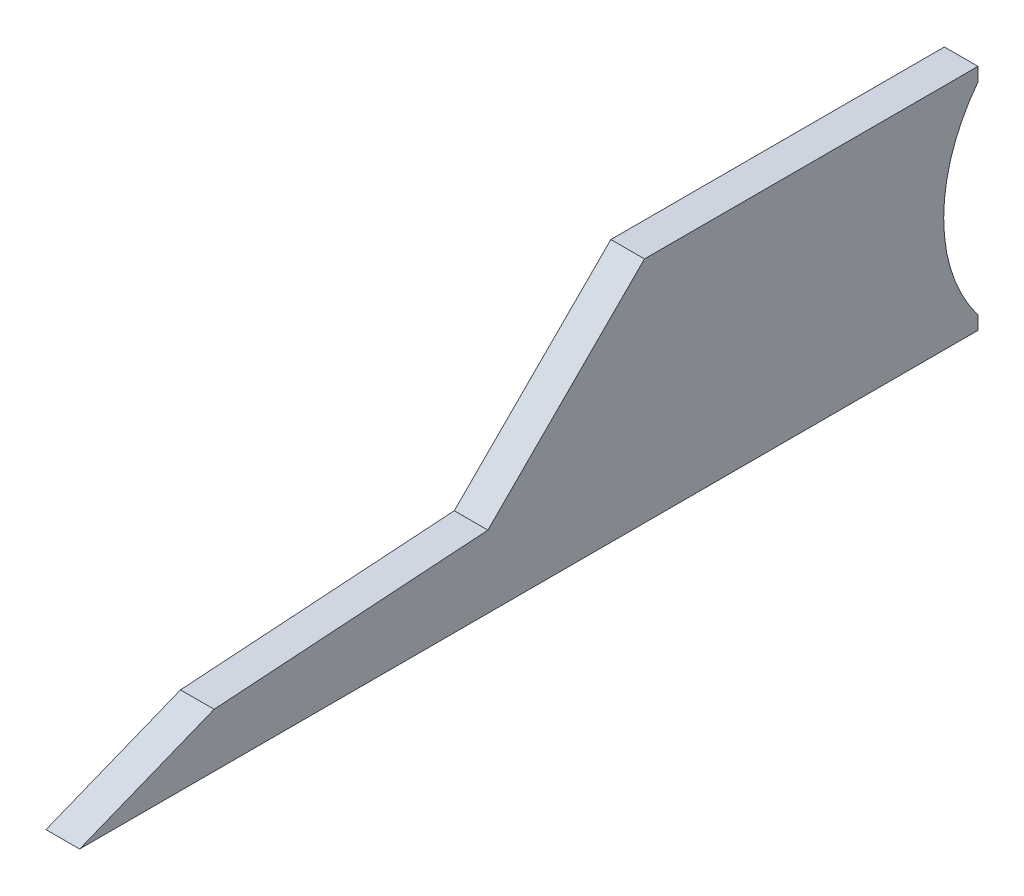
SolidWorks part; units mm, degrees
ref_plane "Front Plane" through (0, 0, 0) normal (0, 0, 1) x (1, 0, 0)
ref_plane "Top Plane" through (0, 0, 0) normal (0, 1, 0) x (1, 0, 0)
ref_plane "Right Plane" through (0, 0, 0) normal (1, 0, 0) x (0, 0, -1)
sketch "Sketch1" plane through (0, 0, 0) normal (1, 0, 0) x (0, 0, -1)
  line L0 (-106.172, 0) -> (-62.992, 43.18)
  line L1 (0, 0) -> (-106.172, 0)
  line L2 (0, 0) -> (0, 2.54)
  line L3 (0, 43.18) -> (-62.992, 43.18)
  line L5 (0, 40.64) -> (-65.532, 40.64) construction
  line L6 (0, 2.54) -> (-103.632, 2.54) construction
  line L7 (0, 40.64) -> (0, 43.18)
  arc A0 (0, 40.64) -> (0, 2.54) centre (24.7621, 21.59) ccw
  point P11 (0, 0)
  dimension "D4" = 62.484
  dimension "D1" = 43.18
  dimension "D2" = 106.172
  dimension "D3" = 45
  dimension "D5" = 2.54
  dimension "D6" = 2.54
extrude "Boss-Extrude1" add sketch "Sketch1" along normal blind 6.35
sketch "Sketch2" plane through (6.35, 0, 0) normal (1, 0, 0) x (0, 0, -1)
  line L0 (-106.172, 0) -> (0, 0) construction
  line L1 (-68.072, 0) -> (-169.672, 0)
  line L2 (-169.672, 0) -> (-144.272, 10.16)
  line L3 (-144.272, 10.16) -> (-68.072, 15.24)
  line L4 (-68.072, 15.24) -> (-68.072, 0)
  point P7 (0, 0)
  point P8 (-125.7874, 5.0635)
  point P9 (-116.6648, 6.0699)
  dimension "D1" = 15.24
  dimension "D2" = 25.4
  dimension "D3" = 10.16
  dimension "D4" = 38.1
  dimension "D5" = 76.2
extrude "Boss-Extrude2" add sketch "Sketch2" against normal up to surface (6.35 mm away) up to face at (0, 21.59, 29.274)
